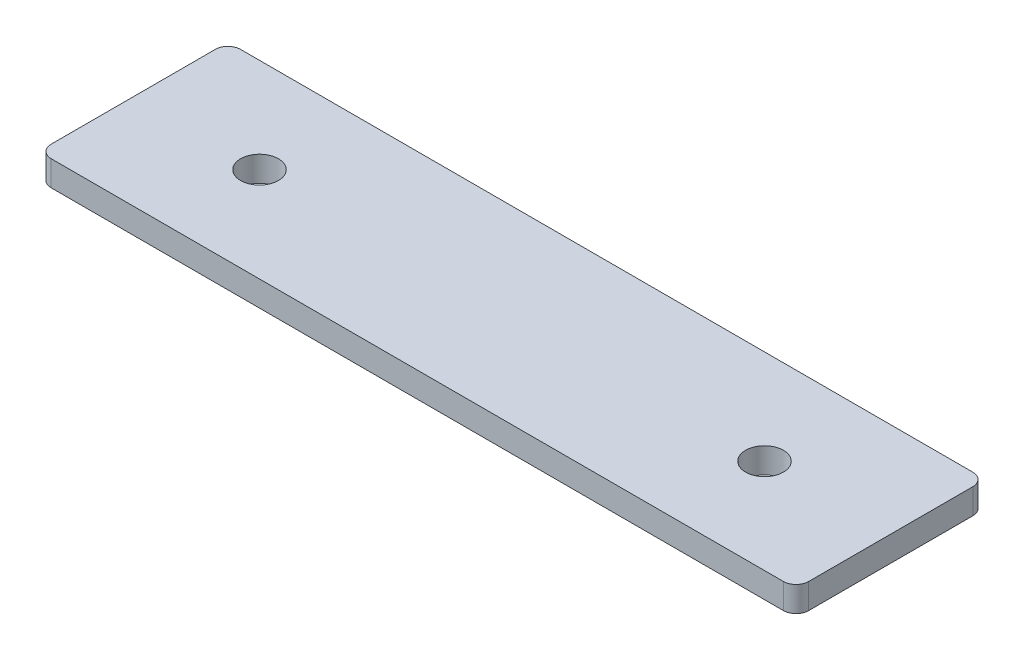
SolidWorks part; units mm, degrees
ref_plane "Front Plane" through (0, 0, 0) normal (0, 0, 1) x (1, 0, 0)
ref_plane "Top Plane" through (0, 0, 0) normal (0, 1, 0) x (1, 0, 0)
ref_plane "Right Plane" through (0, 0, 0) normal (1, 0, 0) x (0, 0, -1)
sketch "Sketch1" plane through (0, 0, 0) normal (0, 1, 0) x (1, 0, 0)
  line L0 (60, 7.5) -> (50, 7.5)
  line L1 (0, 0) -> (60, 0)
  line L2 (0, 0) -> (0, 15)
  line L3 (0, 15) -> (60, 15)
  line L4 (60, 0) -> (60, 15)
  line L5 (50, 7.5) -> (10, 7.5)
  circle A0 centre (50, 7.5) radius 1.5
  circle A1 centre (10, 7.5) radius 1.5
  dimension "D4" = 3
  dimension "D1" = 15
  dimension "D2" = 60
  dimension "D3" = 10
  dimension "D5" = 40
extrude "Boss-Extrude1" add sketch "Sketch1" along normal blind 2
fillet "Fillet1" radius 1 4 edges at (60, 1, -15) (60, 1, 0) (0, 1, 0) (0, 1, -15)
